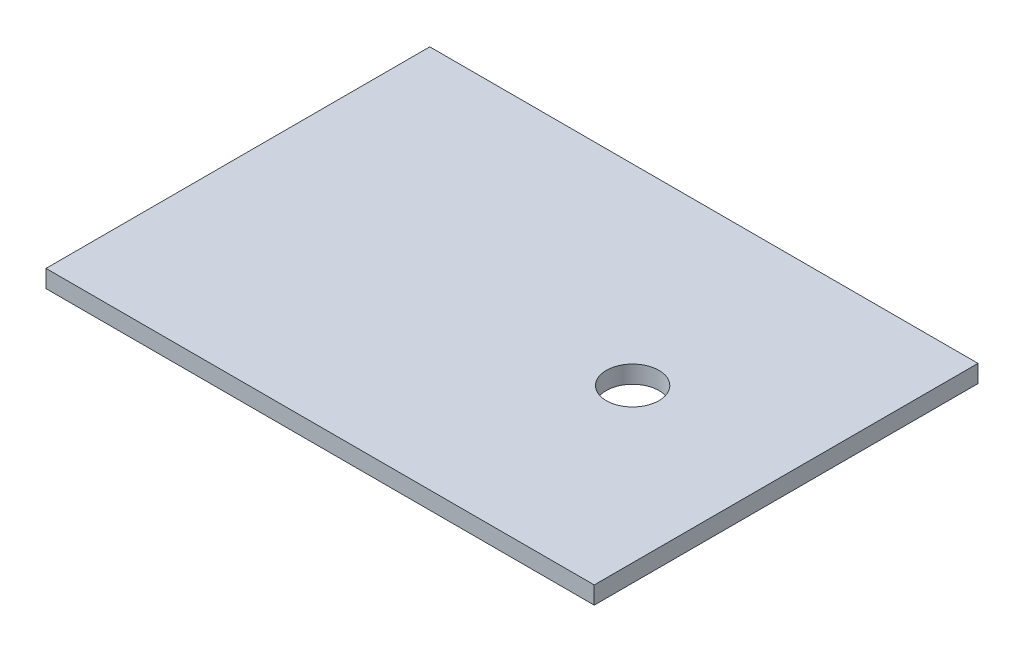
SolidWorks part; units mm, degrees
material "Balsa"
ref_plane "Front Plane" through (0, 0, 0) normal (0, 0, 1) x (1, 0, 0)
ref_plane "Top Plane" through (0, 0, 0) normal (0, 1, 0) x (1, 0, 0)
ref_plane "Right Plane" through (0, 0, 0) normal (1, 0, 0) x (0, 0, -1)
sketch "Sketch1" plane through (0, 0, 0) normal (0, 1, 0) x (1, 0, 0)
  line L0 (-125, -87.5) -> (125, 87.5) construction
  line L1 (-125, -87.5) -> (125, -87.5)
  line L2 (-125, -87.5) -> (-125, 87.5)
  line L3 (-125, 87.5) -> (125, 87.5)
  line L4 (125, -87.5) -> (125, 87.5)
  line L5 (-125, 87.5) -> (125, -87.5) construction
  line L6 (125, 0) -> (55, 0) construction
  circle A0 centre (55, 0) radius 12
  point P4 (0, 0)
  dimension "D3" = 24
  dimension "D1" = 250
  dimension "D2" = 175
  dimension "D5" = 70
extrude "Boss-Extrude1" add sketch "Sketch1" along normal blind 8
